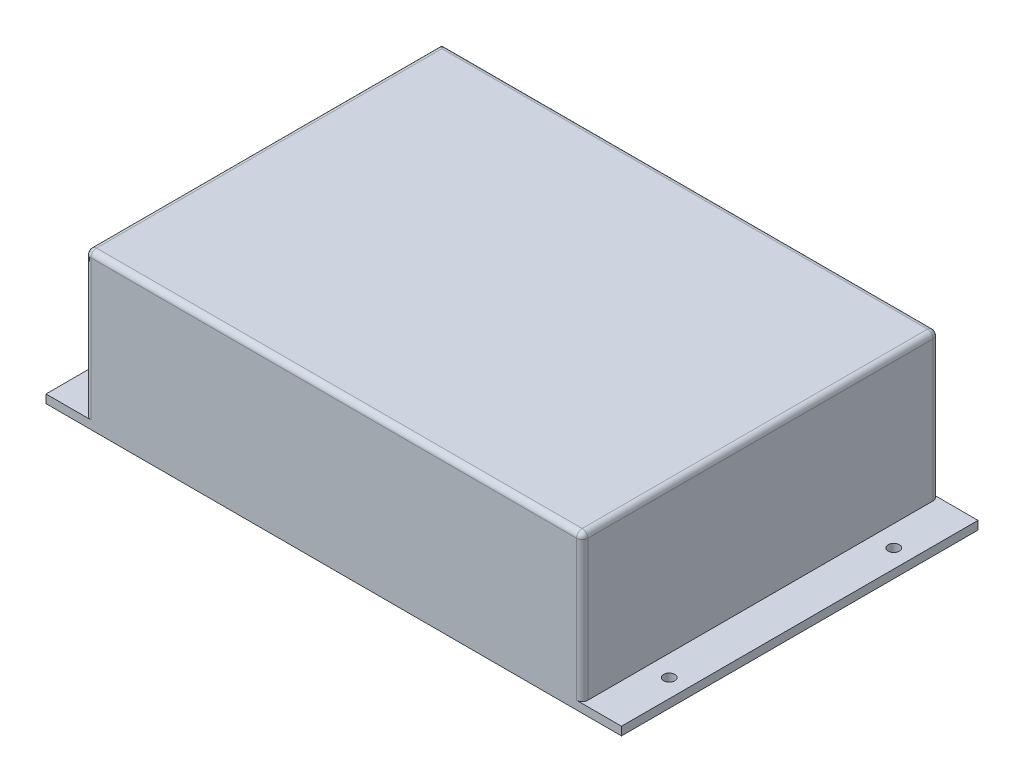
SolidWorks part; units mm, degrees
ref_plane "前视基准面" through (0, 0, 0) normal (0, 0, 1) x (1, 0, 0)
ref_plane "上视基准面" through (0, 0, 0) normal (0, 1, 0) x (1, 0, 0)
ref_plane "右视基准面" through (0, 0, 0) normal (1, 0, 0) x (0, 0, -1)
sketch "草图2" plane through (0, 0, 0) normal (0, 1, 0) x (1, 0, 0)
  line L1 (-102.5, 63.5) -> (102.5, 63.5)
  line L2 (-102.5, 63.5) -> (-102.5, -63.5)
  line L3 (-102.5, -63.5) -> (102.5, -63.5)
  line L4 (102.5, 63.5) -> (102.5, -63.5)
  circle A0 centre (-96, 40) radius 2
  circle A1 centre (96, 40) radius 2
  circle A2 centre (96, -40) radius 2
  circle A3 centre (-96, -40) radius 2
  dimension "D5" = 4
  dimension "D1" = 205
  dimension "D2" = 127
  dimension "D3" = 102.5
  dimension "D4" = 63.5
  dimension "D6" = 23.5
  dimension "D7" = 6.5
  dimension "D8" = 2
  dimension "D9" = 2
extrude "凸台-拉伸1" add sketch "草图2" along normal blind 3
sketch "草图3" plane through (0, 3, 0) normal (0, 1, 0) x (1, 0, 0)
  line L0 (102.5, 63.5) -> (-102.5, 63.5) construction
  line L1 (-88.5, 63.5) -> (88.5, 63.5)
  line L2 (-88.5, 63.5) -> (-88.5, -63.5)
  line L3 (-88.5, -63.5) -> (88.5, -63.5)
  line L4 (88.5, 63.5) -> (88.5, -63.5)
  line L5 (-102.5, -63.5) -> (102.5, -63.5) construction
  line L6 (-102.5, 63.5) -> (-102.5, -63.5) construction
  dimension "D1" = 177
  dimension "D2" = 14
extrude "凸台-拉伸2" add sketch "草图3" along normal blind 52
fillet "圆角1" radius 2 7 edges at (0, 55, -63.5) (88.5, 29, -63.5) (88.5, 55, 0) (88.5, 29, 63.5) (0, 55, 63.5) (-88.5, 29, 63.5) (-88.5, 55, 0)
